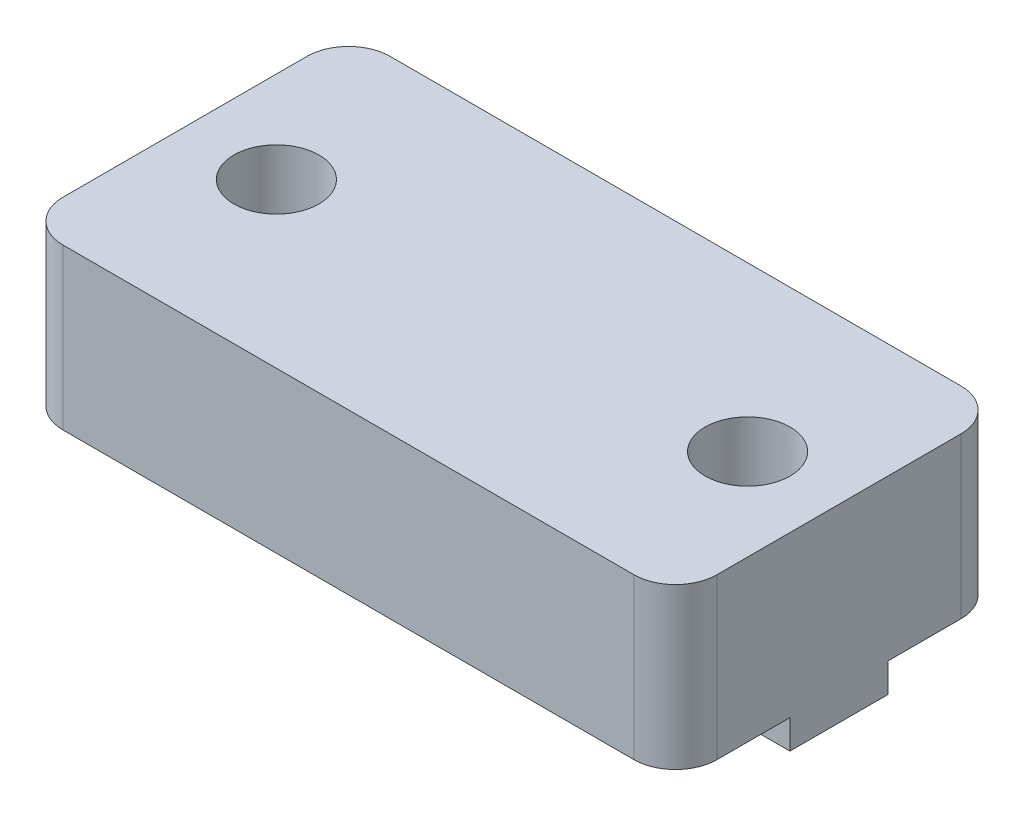
SolidWorks part; units mm, degrees
material "ABS"
ref_plane "Front Plane" through (0, 0, 0) normal (0, 0, 1) x (1, 0, 0)
ref_plane "Top Plane" through (0, 0, 0) normal (0, 1, 0) x (1, 0, 0)
ref_plane "Right Plane" through (0, 0, 0) normal (1, 0, 0) x (0, 0, -1)
sketch "Sketch1" plane through (0, 0, 0) normal (1, 0, 0) x (0, 0, -1)
  line L0 (-10, 4.9) -> (10, 4.9)
  line L1 (-10, 4.9) -> (-10, -4.9)
  line L2 (10, 4.9) -> (10, -4.9)
  line L3 (-10, -4.9) -> (-3, -4.9)
  line L4 (-10, 4.9) -> (10, -4.9) construction
  line L5 (10, 4.9) -> (-10, -4.9) construction
  line L6 (3, -4.9) -> (3, -6.678)
  line L7 (3, -6.678) -> (-3, -6.678)
  line L8 (-3, -6.678) -> (-3, -4.9)
  line L9 (3, -4.9) -> (10, -4.9)
  point P1 (0, 0)
  point P3 (0, -6.678)
  dimension "D1" = 9.8
  dimension "D2" = 20
  dimension "D3" = 6
  dimension "D4" = 1.778
  dimension "D5" = 90
  dimension "D6" = 90
extrude "Boss-Extrude1" add sketch "Sketch1" along normal mid plane 40
sketch "Sketch2" plane through (0, 4.9, 0) normal (0, 1, 0) x (1, 0, 0)
  line L0 (0, 10) -> (0, -10) construction
  line L1 (20, 10) -> (-20, 10) construction
  line L2 (20, -10) -> (-20, -10) construction
  line L3 (-20, 10) -> (-20, -10) construction
  circle A0 centre (-14.412, 0) radius 2.6
  circle A1 centre (14.412, 0) radius 2.6
  dimension "D2" = 5.2
  dimension "D1" = 5.588
extrude "Cut-Extrude1" cut sketch "Sketch2" against normal up to surface (11.578 mm away) up to face at (0, -6.678, 0)
fillet "Fillet1" radius 2.54 4 edges at (-20, 0, -10) (20, 0, -10) (20, 0, 10) (-20, 0, 10)
